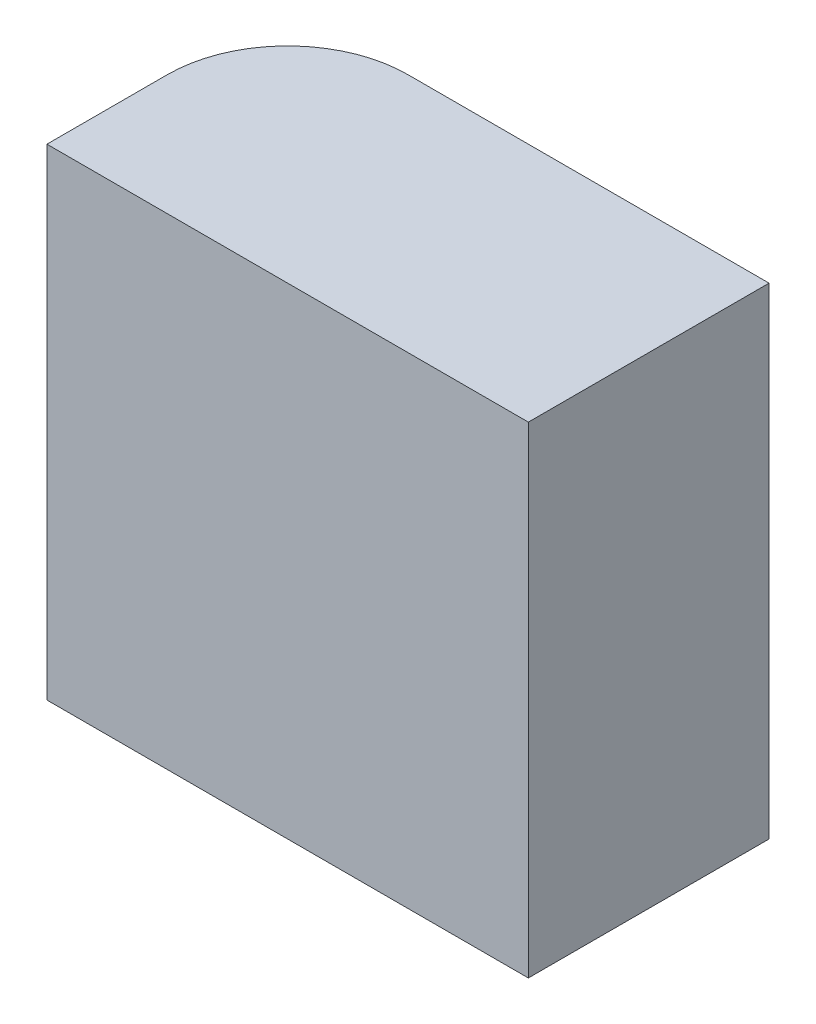
SolidWorks part; units mm, degrees
ref_plane "Přední rovina" through (0, 0, 0) normal (0, 0, 1) x (1, 0, 0)
ref_plane "Horní rovina" through (0, 0, 0) normal (0, 1, 0) x (1, 0, 0)
ref_plane "Pravá rovina" through (0, 0, 0) normal (1, 0, 0) x (0, 0, -1)
sketch "Sketch1" plane through (0, 0, 0) normal (0, 1, 0) x (1, 0, 0)
  line L0 (0, 0) -> (15, 0)
  line L1 (-5, -10) -> (15, -10)
  line L2 (-5, -10) -> (-5, -5)
  line L4 (15, -10) -> (15, 0)
  arc A0 (-5, -5) -> (0, 0) centre (0, -5) cw
  point P1 (2.6369, -10.8234)
  dimension "D1" = 5
  dimension "D2" = 20
  dimension "D3" = 10
extrude "Boss-Extrude1" add sketch "Sketch1" along normal blind 20
equation "\"R\"= 5'Radius"
equation "\"H\"= 20'Extrude height"
equation "\"D1@Boss-Extrude1\"=\"H\""
equation "\"D2@Sketch1\"=\"R\"*4"
equation "\"D3@Sketch1\"=\"R\"*2mm"
